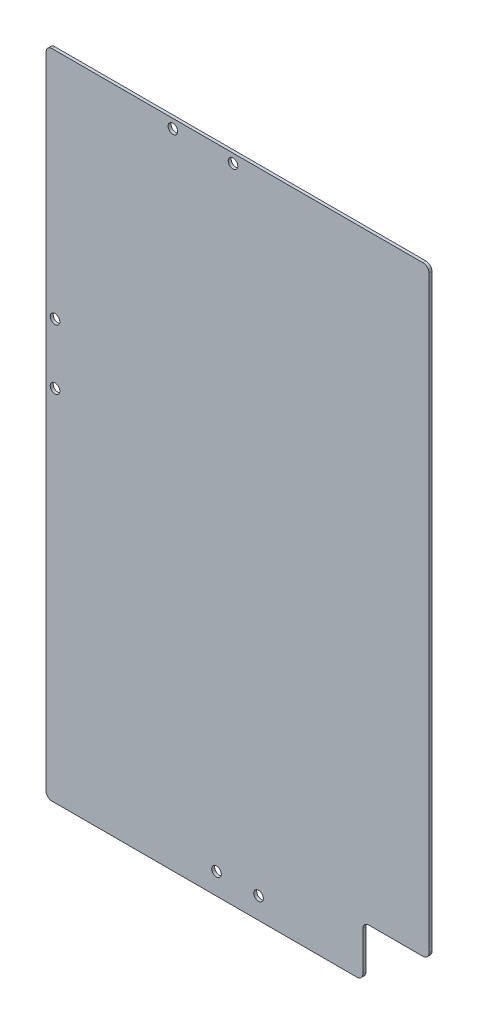
SolidWorks part; units mm, degrees
material "Thornel Mat VMA"
ref_plane "前视基准面" through (0, 0, 0) normal (0, 0, 1) x (1, 0, 0)
ref_plane "上视基准面" through (0, 0, 0) normal (0, 1, 0) x (1, 0, 0)
ref_plane "右视基准面" through (0, 0, 0) normal (1, 0, 0) x (0, 0, -1)
other "Configuration Table"
sketch "草图1" plane through (0, 0, 0) normal (0, 0, 1) x (1, 0, 0)
  line L0 (-21.5, 89.5) -> (-1.5, 89.5) construction
  line L1 (-63.75, -92.5) -> (63.75, -92.5)
  line L2 (-63.75, -92.5) -> (-63.75, 92.5)
  line L3 (-63.75, 92.5) -> (63.75, 92.5)
  line L4 (63.75, -92.5) -> (63.75, 92.5)
  line L5 (-63.75, -92.5) -> (63.75, 92.5) construction
  line L6 (-63.75, 92.5) -> (63.75, -92.5) construction
  line L7 (-60.75, 15) -> (-60.75, -5) construction
  circle A0 centre (-21.5, 89.5) radius 1.6
  circle A1 centre (-1.5, 89.5) radius 1.6
  circle A2 centre (-60.75, 15) radius 1.6
  circle A3 centre (-60.75, -5) radius 1.6
  point P0 (0, 0)
  dimension "D3" = 42.25
  dimension "D5" = 3.2
  dimension "D7" = 77.5
  dimension "D8" = 3
  dimension "D9" = 3.2
  dimension "D1" = 185
  dimension "D2" = 127.5
  dimension "D4" = 20
  dimension "D6" = 3
  dimension "D10" = 20
extrude "凸台-拉伸1" add sketch "草图1" along normal blind 1
sketch "草图2" plane through (0, 0, 1) normal (0, 0, 1) x (1, 0, 0)
  line L1 (-63.75, -92.5) -> (63.75, -92.5)
  line L2 (-63.75, -92.5) -> (-63.75, -127.5)
  line L3 (-63.75, -127.5) -> (63.75, -127.5)
  line L4 (63.75, -92.5) -> (63.75, -127.5)
  dimension "D1" = 35
extrude "凸台-拉伸2" add sketch "草图2" against normal up to surface (1 mm away) up to face at (-59.15, 15, 0)
sketch "草图3" plane through (0, 0, 0) normal (0, 0, -1) x (-1, 0, 0)
  line L0 (0, -127.5) -> (0, 92.5) construction
  line L1 (63.75, -127.5) -> (-63.75, -127.5) construction
  line L2 (-63.75, 92.5) -> (63.75, 92.5) construction
  line L3 (-7, -117.4) -> (7, -117.4) construction
  circle A0 centre (-7, -117.4) radius 1.6
  circle A1 centre (7, -117.4) radius 1.6
  dimension "D1" = 14
  dimension "D2" = 3.2
  dimension "D3" = 10.1
extrude "切除-拉伸1" cut sketch "草图3" against normal blind 10
sketch "草图4" plane through (0, 0, 0) normal (0, 0, -1) x (-1, 0, 0)
  line L0 (63.75, 92.5) -> (63.75, -127.5) construction
  line L1 (-63.75, -127.5) -> (63.75, -127.5)
  line L2 (-63.75, -127.5) -> (-63.75, -124.5)
  line L3 (-63.75, -124.5) -> (63.75, -124.5)
  line L4 (63.75, -127.5) -> (63.75, -124.5)
  dimension "D1" = 3
extrude "切除-拉伸2" cut sketch "草图4" against normal blind 10
sketch "草图5" plane through (0, 0, 1) normal (0, 0, 1) x (1, 0, 0)
  line L1 (63.75, -124.5) -> (41.75, -124.5)
  line L2 (63.75, -124.5) -> (63.75, -107.5)
  line L3 (63.75, -107.5) -> (41.75, -107.5)
  line L4 (41.75, -124.5) -> (41.75, -107.5)
  dimension "D1" = 17
  dimension "D2" = 22
extrude "切除-拉伸3" cut sketch "草图5" against normal blind 10
fillet "圆角2" radius 2 6 edges at (-63.75, -124.5, 0.5) (63.75, 92.5, 0.5) (63.75, -107.5, 0.5) (41.75, -107.5, 0.5) (41.75, -124.5, 0.5) (-63.75, 92.5, 0.5)
